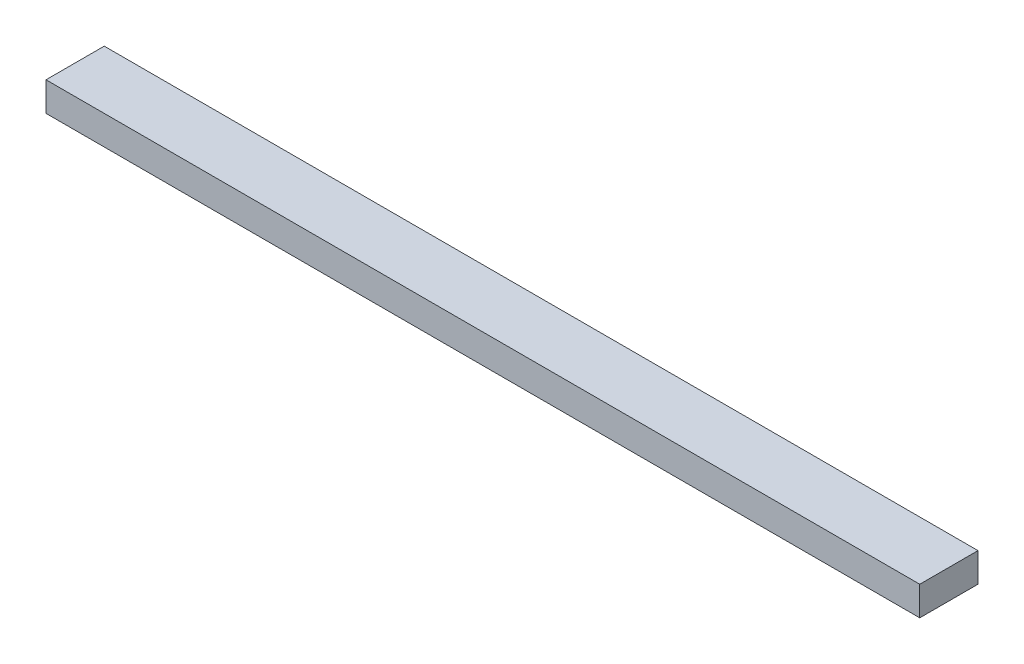
SolidWorks part; units mm, degrees
ref_plane "Front Plane" through (0, 0, 0) normal (0, 0, 1) x (1, 0, 0)
ref_plane "Top Plane" through (0, 0, 0) normal (0, 1, 0) x (1, 0, 0)
ref_plane "Right Plane" through (0, 0, 0) normal (1, 0, 0) x (0, 0, -1)
sketch "Sketch2" plane through (0, 0, 0) normal (0, 1, 0) x (1, 0, 0)
  line L1 (-150, 10) -> (150, 10)
  line L2 (-150, 10) -> (-150, -10)
  line L3 (-150, -10) -> (150, -10)
  line L4 (150, 10) -> (150, -10)
  line L5 (-150, 10) -> (150, -10) construction
  line L6 (-150, -10) -> (150, 10) construction
  point P0 (0, 0)
  dimension "D1" = 20
  dimension "D2" = 300
extrude "Boss-Extrude1" add sketch "Sketch2" along normal blind 10
